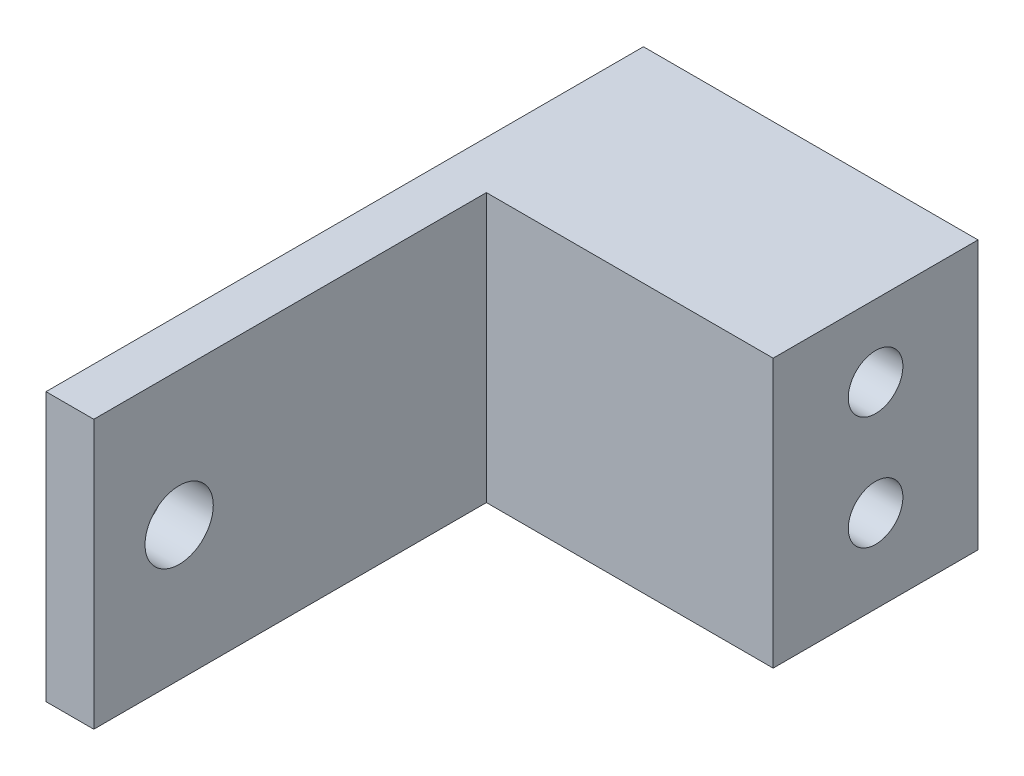
SolidWorks part; units mm, degrees
ref_plane "Alzado" through (0, 0, 0) normal (0, 0, 1) x (1, 0, 0)
ref_plane "Planta" through (0, 0, 0) normal (0, 1, 0) x (1, 0, 0)
ref_plane "Vista lateral" through (0, 0, 0) normal (1, 0, 0) x (0, 0, -1)
sketch "Croquis1" plane through (26.698, 0, 0) normal (-1, 0, 0) x (0, 0, 1)
  line L0 (-45.3448, -101.1174) -> (-45.3448, -107.1174) construction
  line L1 (-51.3448, -107.1174) -> (-45.3448, -107.1174)
  line L2 (-51.3448, -107.1174) -> (-51.3448, -99.2531)
  line L3 (-51.3448, -99.2531) -> (-45.3448, -99.2531)
  line L4 (-45.3448, -107.1174) -> (-45.3448, -99.2531)
  line L5 (-45.3448, -99.2531) -> (-51.3448, -99.2531) construction
extrude "Saliente-Extruir1" add sketch "Croquis1" along normal blind 9.8
sketch "Croquis2" plane through (0, 0, -45.3448) normal (0, 0, 1) x (1, 0, 0)
  line L0 (16.898, -99.2531) -> (26.698, -99.2531) construction
  line L1 (16.898, -107.1174) -> (18.298, -107.1174)
  line L2 (16.898, -107.1174) -> (16.898, -99.2531)
  line L3 (16.898, -99.2531) -> (18.298, -99.2531)
  line L4 (18.298, -107.1174) -> (18.298, -99.2531)
  dimension "D1" = 1.4
extrude "Saliente-Extruir2" add sketch "Croquis2" along normal blind 11.5
sketch "Croquis3" plane through (18.298, 0, 0) normal (1, 0, 0) x (0, 0, -1)
  line L0 (33.8448, -103.1852) -> (36.3448, -103.1852) construction
  line L1 (33.8448, -107.1174) -> (33.8448, -99.2531) construction
  circle A0 centre (36.3448, -103.1852) radius 1
  point P3 (36.2745, -103.1852)
  dimension "D1" = 2
  dimension "D2" = 2.5
extrude "Cortar-Extruir1" cut sketch "Croquis3" against normal up to surface (1.4 mm away) contours A0 up to face at (16.898, -103.1852, -42.5948)
sketch "Croquis4" plane through (26.698, 0, 0) normal (1, 0, 0) x (0, 0, -1)
  circle A0 centre (48.3448, -104.6778) radius 0.8
  circle A1 centre (48.3448, -101.3593) radius 0.8
hole_wizard "Taladro roscado M21" positions "Croquis5" profile "Croquis6" tap size "M2" standard "ISO"
sketch "Croquis5" plane through (26.698, 0, 0) normal (1, 0, 0) x (0, 0, -1)
  point P0 (48.3448, -104.6778)
  point P3 (48.3448, -101.3593)
sketch "Croquis6" plane through (26.698, -104.6778, -48.3448) normal (0, 1, 0) x (0, 0, -1)
  line L0 (0, 0) -> (0, 13.4807)
  line L1 (0, 13.4807) -> (0.8, 13)
  line L2 (0.8, 13) -> (0.8, 0)
  line L5 (0.8, 0) -> (0, 0)
  line L10 (0, 13.4807) -> (-0.8, 13) construction
  line L11 (0, -6.35) -> (0, 107.95) construction
  dimension "Diámetro de perforador para roscar" = 1.6
  dimension "Profundidad de perforador para roscar" = 13
  dimension "Ángulo de perforador" = 118
